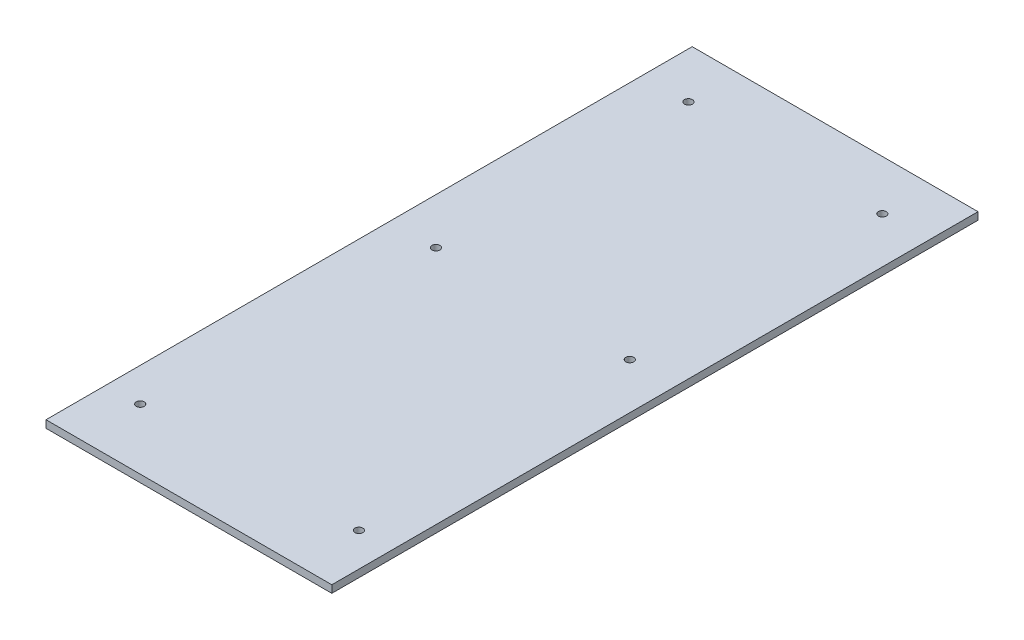
SolidWorks part; units mm, degrees
ref_plane "Plan de face" through (0, 0, 0) normal (0, 0, 1) x (1, 0, 0)
ref_plane "Plan de dessus" through (0, 0, 0) normal (0, 1, 0) x (1, 0, 0)
ref_plane "Plan de droite" through (0, 0, 0) normal (1, 0, 0) x (0, 0, -1)
sketch "Esquisse1" plane through (0, 0, 0) normal (0, 1, 0) x (1, 0, 0)
  line L1 (-34.9255, 37.0612) -> (80.0745, 37.0612)
  line L2 (-34.9255, 37.0612) -> (-34.9255, -222.9388)
  line L3 (-34.9255, -222.9388) -> (80.0745, -222.9388)
  line L4 (80.0745, 37.0612) -> (80.0745, -222.9388)
  dimension "D1" = 115
  dimension "D2" = 260
extrude "Boss.-Extru.1" add sketch "Esquisse1" along normal blind 3 contours L1 L4 L3 L2
sketch "Esquisse2" plane through (0, 3, 0) normal (0, 1, 0) x (1, 0, 0)
  line L0 (-34.9255, -222.9388) -> (80.0745, -222.9388) construction
  line L2 (-34.9255, 37.0612) -> (-34.9255, -222.9388) construction
  line L3 (-34.9255, 37.0612) -> (80.0745, 37.0612) construction
  circle A0 centre (-21.4255, -198.5388) radius 1.6
  circle A1 centre (66.5745, -198.5388) radius 1.6
  circle A2 centre (-16.4255, -84.5388) radius 1.6
  circle A3 centre (61.5745, -84.5388) radius 1.6
  circle A4 centre (-16.4255, 17.0612) radius 1.6
  circle A5 centre (61.5745, 17.0612) radius 1.6
  dimension "D3" = 3.2
  dimension "D4" = 3.2
  dimension "D9" = 3.2
  dimension "D10" = 3.2
  dimension "D17" = 3.2
  dimension "D18" = 3.2
  dimension "D1" = 24.4
  dimension "D2" = 24.4
  dimension "D5" = 88
  dimension "D6" = 13.5
  dimension "D7" = 114
  dimension "D8" = 114
  dimension "D11" = 78
  dimension "D12" = 18.5
  dimension "D13" = 20
  dimension "D14" = 20
  dimension "D15" = 78
  dimension "D16" = 18.5
extrude "Enlèv. mat.-Extru.1" cut sketch "Esquisse2" against normal up to next
equation "\"D1@Esquisse2\"=10.4+14"
equation "\"D5@Esquisse2\"=110-22"
equation "\"D6@Esquisse2\"=(115-88)/2"
equation "\"D7@Esquisse2\"=142-14-14"
equation "\"D13@Esquisse2\"=6+14"
